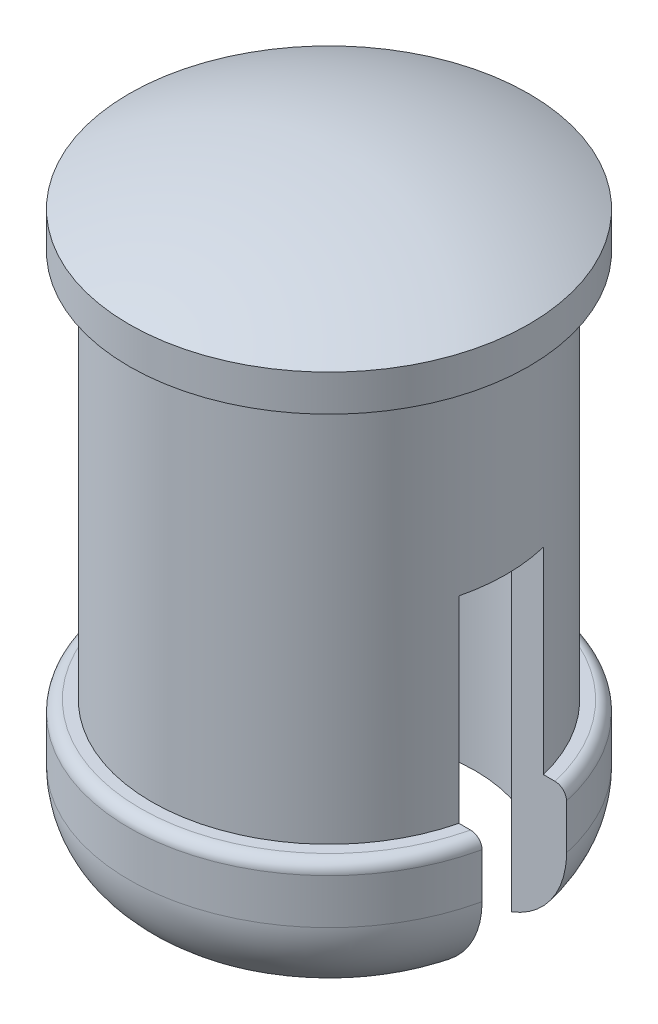
SolidWorks part; units mm, degrees
ref_plane "前视基准面" through (0, 0, 0) normal (0, 0, 1) x (1, 0, 0)
ref_plane "上视基准面" through (0, 0, 0) normal (0, 1, 0) x (1, 0, 0)
ref_plane "右视基准面" through (0, 0, 0) normal (1, 0, 0) x (0, 0, -1)
sketch "草图3" plane through (0, 0, 0) normal (1, 0, 0) x (0, 0, -1)
  line L0 (0, 28.2119) -> (0, -26.3712) construction
  line L1 (3.55, 10.0476) -> (3.55, 9.4)
  line L2 (3.55, 9.4) -> (3.15, 9.4)
  line L3 (3.15, 9.4) -> (3.15, 2.5)
  line L4 (3.15, 2.5) -> (3.35, 2.5)
  line L5 (0, 0) -> (2.05, 0)
  line L6 (3.55, 1.5) -> (3.55, 2.3)
  line L7 (0, 10.9) -> (0, 0)
  arc A0 (0, 10.9) -> (3.55, 10.0476) centre (0, 3.0813) cw
  arc A1 (3.55, 2.3) -> (3.35, 2.5) centre (3.35, 2.3) ccw
  arc A2 (2.05, 0) -> (3.55, 1.5) centre (2.05, 1.5) ccw
  dimension "D6" = 0.2
  dimension "D7" = 1.5
  dimension "D1" = 10.9
  dimension "D2" = 1.5
  dimension "D3" = 3.55
  dimension "D4" = 6.9
  dimension "D5" = 3.15
revolve "旋转1" add sketch "草图3" angle 360 about L0
sketch "草图4" plane through (0, 0, 0) normal (0, -1, 0) x (1, 0, 0)
  circle A0 centre (0, 0) radius 2.6
  dimension "D1" = 5.2
extrude "切除-拉伸1" cut sketch "草图4" against normal blind 9
sketch "草图5" plane through (0, 0, 0) normal (0, 1, 0) x (1, 0, 0)
  line L0 (-3.9021, 0) -> (4.5084, 0) construction
  line L1 (-6.4079, -0.75) -> (6.2539, -0.75)
  line L2 (-6.4079, -0.75) -> (-6.4079, 0.75)
  line L3 (-6.4079, 0.75) -> (6.2539, 0.75)
  line L4 (6.2539, -0.75) -> (6.2539, 0.75)
  dimension "D1" = 1.5
extrude "切除-拉伸3" cut sketch "草图5" along normal blind 6
